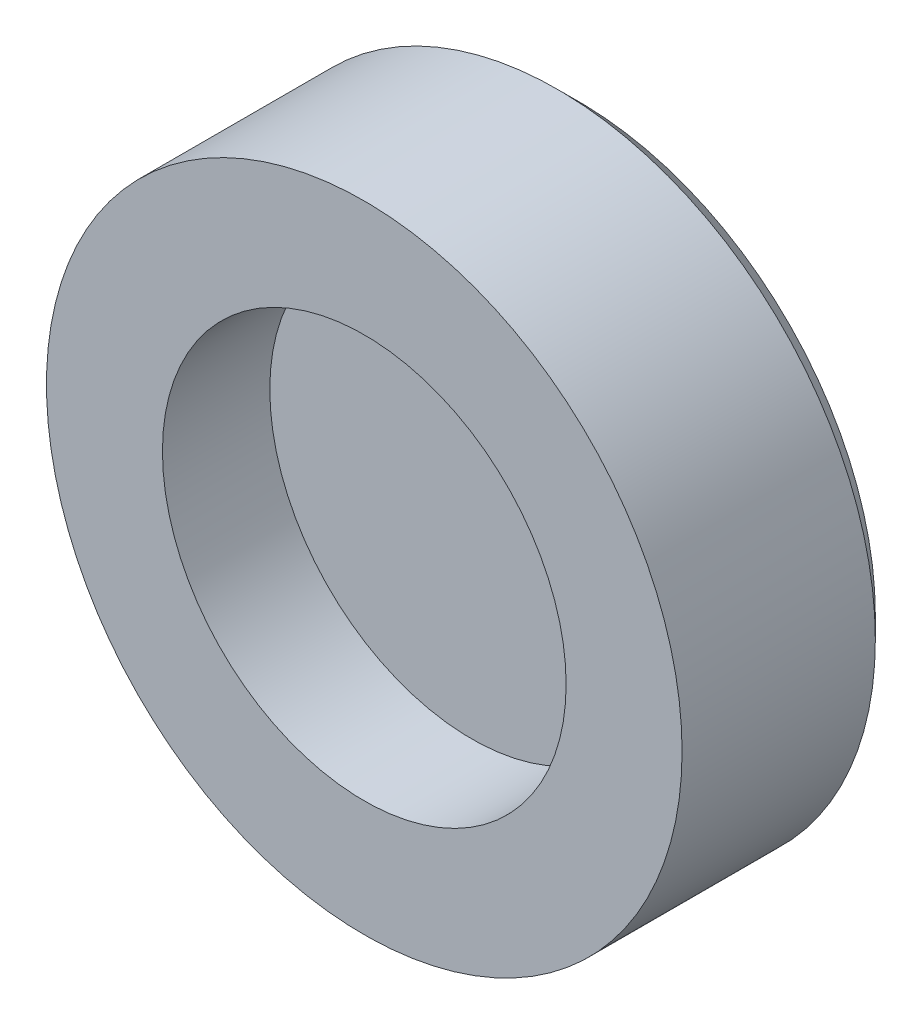
SolidWorks part; units mm, degrees
ref_plane "Front Plane" through (0, 0, 0) normal (0, 0, 1) x (1, 0, 0)
ref_plane "Top Plane" through (0, 0, 0) normal (0, 1, 0) x (1, 0, 0)
ref_plane "Right Plane" through (0, 0, 0) normal (1, 0, 0) x (0, 0, -1)
sketch "Sketch1" plane through (0, 0, 0) normal (0, 1, 0) x (1, 0, 0)
  line L0 (0, -16.8198) -> (0, 12.006) construction
  line L1 (-20.0004, 0) -> (19.5992, 0) construction
  line L2 (-7.4, -5) -> (-4.7, -5)
  line L3 (-4.7, -5) -> (-4.7, -2.5)
  line L4 (-4.7, -2.5) -> (0, -2.5)
  line L5 (-7.4, -5) -> (-7.4, 0)
  line L6 (-7.4, 0) -> (0, 0)
  line L7 (0, -2.5) -> (0, 0)
  point P11 (0, -2.4069)
  point P12 (-6.05, -5)
  dimension "D1" = 7.4
  dimension "D2" = 4.7
  dimension "D3" = 2.5
  dimension "D4" = 5
revolve "Revolve1" add sketch "Sketch1" angle 360 about L0
chamfer "Chamfer1" distance 0.5 1 edges at (7.4, 0, 0)
